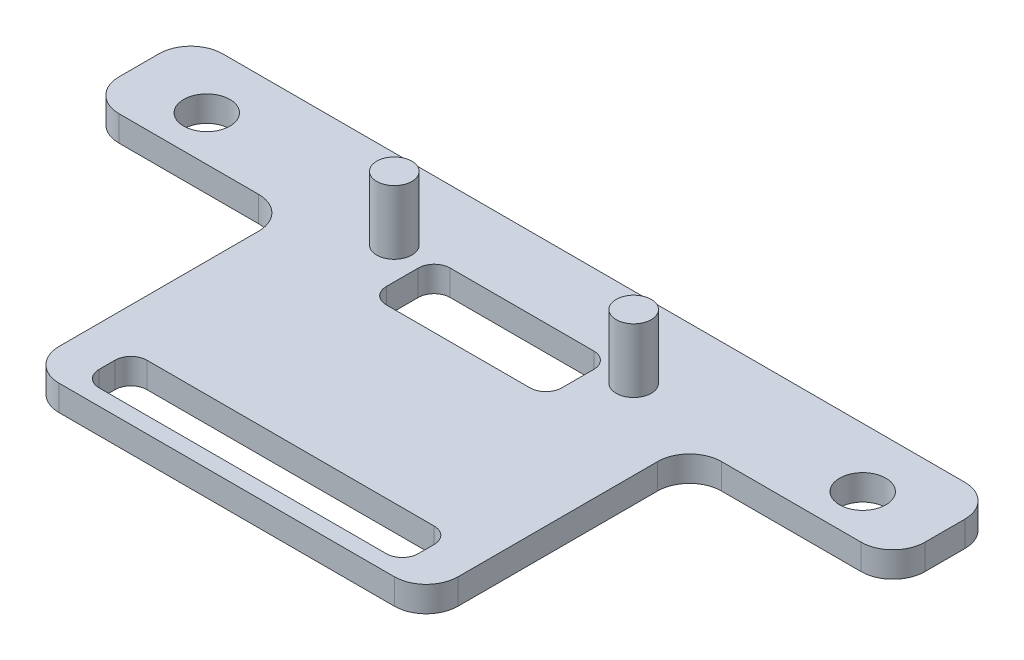
SolidWorks part; units mm, degrees
ref_plane "Ebene vorne" through (0, 0, 0) normal (0, 0, 1) x (1, 0, 0)
ref_plane "Ebene oben" through (0, 0, 0) normal (0, 1, 0) x (1, 0, 0)
ref_plane "Ebene rechts" through (0, 0, 0) normal (1, 0, 0) x (0, 0, -1)
sketch "Skizze1" plane through (0, 0, 0) normal (0, 1, 0) x (1, 0, 0)
  line L0 (25.25, -22.1424) -> (25.25, 0) construction
  line L1 (0, 0) -> (50.5, 0)
  line L2 (0, 0) -> (0, -6.5)
  line L3 (12.75, -23) -> (37.75, -23)
  line L4 (50.5, 0) -> (50.5, -6.5)
  line L5 (0, -6.5) -> (12.75, -6.5)
  line L6 (12.75, -6.5) -> (12.75, -23)
  line L7 (50.5, -6.5) -> (37.75, -6.5)
  line L8 (37.75, -6.5) -> (37.75, -23)
  line L10 (0, -3.7) -> (50.5, -3.7) construction
  circle A0 centre (4.7, -3.7) radius 1.45
  circle A1 centre (45.8, -3.7) radius 1.45
  dimension "D5" = 2.9
  dimension "D7" = 41.1
  dimension "D1" = 50.5
  dimension "D2" = 25
  dimension "D3" = 6.5
  dimension "D4" = 23
  dimension "D6" = 3.7
extrude "Aufsatz-Linear austragen1" add sketch "Skizze1" along normal blind 1.6
fillet "Verrundung1" radius 2 8 edges at (37.75, 0.8, 23) (12.75, 0.8, 23) (12.75, 0.8, 6.5) (37.75, 0.8, 6.5) (50.5, 0.8, 6.5) (50.5, 0.8, 0) (0, 0.8, 6.5) (0, 0.8, 0)
sketch "Skizze2" plane through (0, 1.6, 0) normal (0, 1, 0) x (1, 0, 0)
  line L0 (0, -5) -> (50.5, -5) construction
  line L1 (0, -2) -> (0, -4.5) construction
  line L2 (50.5, -4.5) -> (50.5, -2) construction
  line L3 (48.5, 0) -> (2, 0) construction
  line L4 (25.25, 0) -> (25.25, -23) construction
  line L5 (14.75, -23) -> (35.75, -23) construction
  circle A0 centre (17.75, -5) radius 1.1
  circle A1 centre (32.75, -5) radius 1.1
  dimension "D2" = 2.2
  dimension "D3" = 15
  dimension "D1" = 5
extrude "Aufsatz-Linear austragen2" add sketch "Skizze2" along normal blind 4
sketch "Skizze3" plane through (0, 1.6, 0) normal (0, 1, 0) x (1, 0, 0)
  line L0 (25.25, 0) -> (25.25, -23) construction
  line L1 (19.75, -4.5) -> (30.75, -4.5)
  line L2 (19.75, -4.5) -> (19.75, -8.5)
  line L3 (19.75, -8.5) -> (30.75, -8.5)
  line L4 (30.75, -4.5) -> (30.75, -8.5)
  line L5 (48.5, 0) -> (2, 0) construction
  line L6 (14.75, -23) -> (35.75, -23) construction
  line L7 (17.75, -5) -> (32.75, -5) construction
  line L8 (19.75, -6.5) -> (30.75, -6.5) construction
  dimension "D1" = 1.5
  dimension "D2" = 4
  dimension "D3" = 11
extrude "Schnitt-Linear austragen1" cut sketch "Skizze3" against normal blind 3
fillet "Verrundung2" radius 1 4 edges at (30.75, 0.8, 8.5) (30.75, 0.8, 4.5) (19.75, 0.8, 8.5) (19.75, 0.8, 4.5)
sketch "Skizze4" plane through (0, 1.6, 0) normal (0, 1, 0) x (1, 0, 0)
  line L0 (15.25, -20.5) -> (35.25, -20.5) construction
  line L1 (15.25, -22) -> (35.25, -22)
  line L2 (15.25, -22) -> (15.25, -19)
  line L3 (15.25, -19) -> (35.25, -19)
  line L4 (35.25, -22) -> (35.25, -19)
  line L5 (17.75, -5) -> (33.072, -5) construction
  line L6 (25.25, 0) -> (25.25, -23) construction
  line L7 (48.5, 0) -> (2, 0) construction
  line L8 (14.75, -23) -> (35.75, -23) construction
  point P16 (17.75, -5)
  point P18 (33.072, -5)
  point P19 (0, 0)
  dimension "D1" = 15.5
  dimension "D2" = 20
  dimension "D3" = 3
extrude "Schnitt-Linear austragen2" cut sketch "Skizze4" against normal blind 3
fillet "Verrundung3" radius 1 4 edges at (35.25, 0.8, 22) (35.25, 0.8, 19) (15.25, 0.8, 22) (15.25, 0.8, 19)
